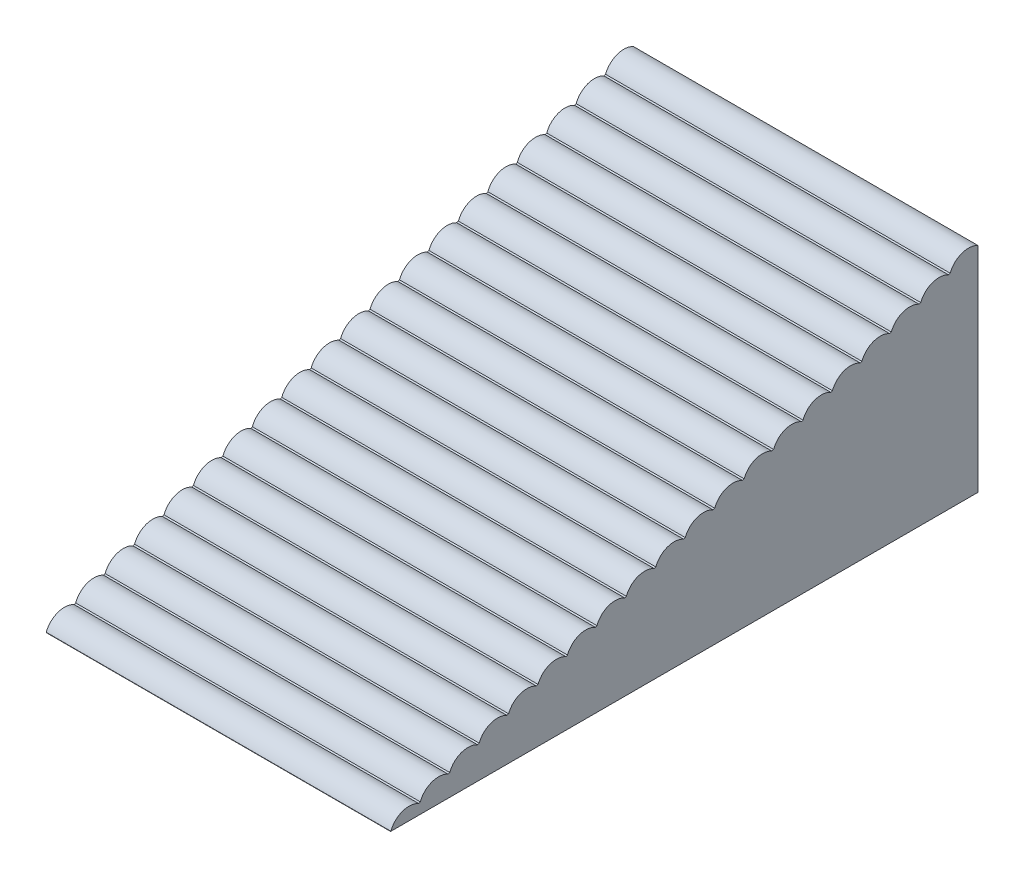
SolidWorks part; units mm, degrees
ref_plane "Front Plane" through (0, 0, 0) normal (0, 0, 1) x (1, 0, 0)
ref_plane "Top Plane" through (0, 0, 0) normal (0, 1, 0) x (1, 0, 0)
ref_plane "Right Plane" through (0, 0, 0) normal (1, 0, 0) x (0, 0, -1)
sketch "Sketch1" plane through (0, 0, 0) normal (1, 0, 0) x (0, 0, -1)
  line L0 (0, 0) -> (15, 5.4596)
  line L1 (15, 5.4596) -> (15, 0)
  line L2 (15, 0) -> (0, 0)
  dimension "D1" = 15
  dimension "D2" = 20
extrude "Boss-Extrude1" add sketch "Sketch1" along normal blind 8.8
sketch "Sketch2" plane through (0, 0, 0) normal (-1, 0, 0) x (0, 0, 1)
  line L0 (-15, 5.4596) -> (-14.2897, 5.201)
  line L20 (-14.2482, 5.1859) -> (-13.5379, 4.9274)
  line L21 (-13.4965, 4.9123) -> (-12.7862, 4.6538)
  line L22 (-12.7447, 4.6387) -> (-12.0344, 4.3802)
  line L23 (-11.993, 4.3651) -> (-11.2826, 4.1065)
  line L24 (-11.2412, 4.0915) -> (-10.5309, 3.8329)
  line L25 (-10.4895, 3.8179) -> (-9.7791, 3.5593)
  line L26 (-9.7377, 3.5442) -> (-9.0274, 3.2857)
  line L27 (-8.986, 3.2706) -> (-8.2756, 3.0121)
  line L28 (-8.2342, 2.997) -> (-7.5239, 2.7385)
  line L29 (-7.4825, 2.7234) -> (-6.7721, 2.4649)
  line L30 (-6.7307, 2.4498) -> (-6.0204, 2.1912)
  line L31 (-5.979, 2.1762) -> (-5.2686, 1.9176)
  line L32 (-5.2272, 1.9025) -> (-4.5169, 1.644)
  line L33 (-4.4754, 1.6289) -> (-3.7651, 1.3704)
  line L34 (-3.7237, 1.3553) -> (-3.0134, 1.0968)
  line L35 (-2.9719, 1.0817) -> (-2.2616, 0.8232)
  line L36 (-2.2202, 0.8081) -> (-1.5098, 0.5495)
  line L37 (-1.4684, 0.5345) -> (-0.7581, 0.2759)
  line L38 (-0.7167, 0.2608) -> (-0.0063, 0.0023)
  arc A20 (-15, 5.4596) -> (-14.2897, 5.201) centre (-14.7568, 5.0227) cw
  arc A21 (-14.2482, 5.1859) -> (-13.5379, 4.9274) centre (-14.005, 4.7491) cw
  arc A22 (-13.4965, 4.9123) -> (-12.7862, 4.6538) centre (-13.2533, 4.4755) cw
  arc A23 (-12.7447, 4.6387) -> (-12.0344, 4.3802) centre (-12.5015, 4.2018) cw
  arc A24 (-11.993, 4.3651) -> (-11.2826, 4.1065) centre (-11.7498, 3.9282) cw
  arc A25 (-11.2412, 4.0915) -> (-10.5309, 3.8329) centre (-10.998, 3.6546) cw
  arc A26 (-10.4895, 3.8179) -> (-9.7791, 3.5593) centre (-10.2463, 3.381) cw
  arc A27 (-9.7377, 3.5442) -> (-9.0274, 3.2857) centre (-9.4945, 3.1074) cw
  arc A28 (-8.986, 3.2706) -> (-8.2756, 3.0121) centre (-8.7428, 2.8338) cw
  arc A29 (-8.2342, 2.997) -> (-7.5239, 2.7385) centre (-7.991, 2.5601) cw
  arc A30 (-7.4825, 2.7234) -> (-6.7721, 2.4649) centre (-7.2392, 2.2865) cw
  arc A31 (-6.7307, 2.4498) -> (-6.0204, 2.1912) centre (-6.4875, 2.0129) cw
  arc A32 (-5.979, 2.1762) -> (-5.2686, 1.9176) centre (-5.7357, 1.7393) cw
  arc A33 (-5.2272, 1.9025) -> (-4.5169, 1.644) centre (-4.984, 1.4657) cw
  arc A34 (-4.4754, 1.6289) -> (-3.7651, 1.3704) centre (-4.2322, 1.1921) cw
  arc A35 (-3.7237, 1.3553) -> (-3.0134, 1.0968) centre (-3.4805, 0.9185) cw
  arc A36 (-2.9719, 1.0817) -> (-2.2616, 0.8232) centre (-2.7287, 0.6448) cw
  arc A37 (-2.2202, 0.8081) -> (-1.5098, 0.5495) centre (-1.977, 0.3712) cw
  arc A38 (-1.4684, 0.5345) -> (-0.7581, 0.2759) centre (-1.2252, 0.0976) cw
  arc A39 (-0.7167, 0.2608) -> (-0.0063, 0.0023) centre (-0.4735, -0.176) cw
  dimension "D1" = 20
extrude "Boss-Extrude3" add sketch "Sketch2" against normal up to surface (8.8 mm away) up to face at (8.8, 1.8199, -10)
